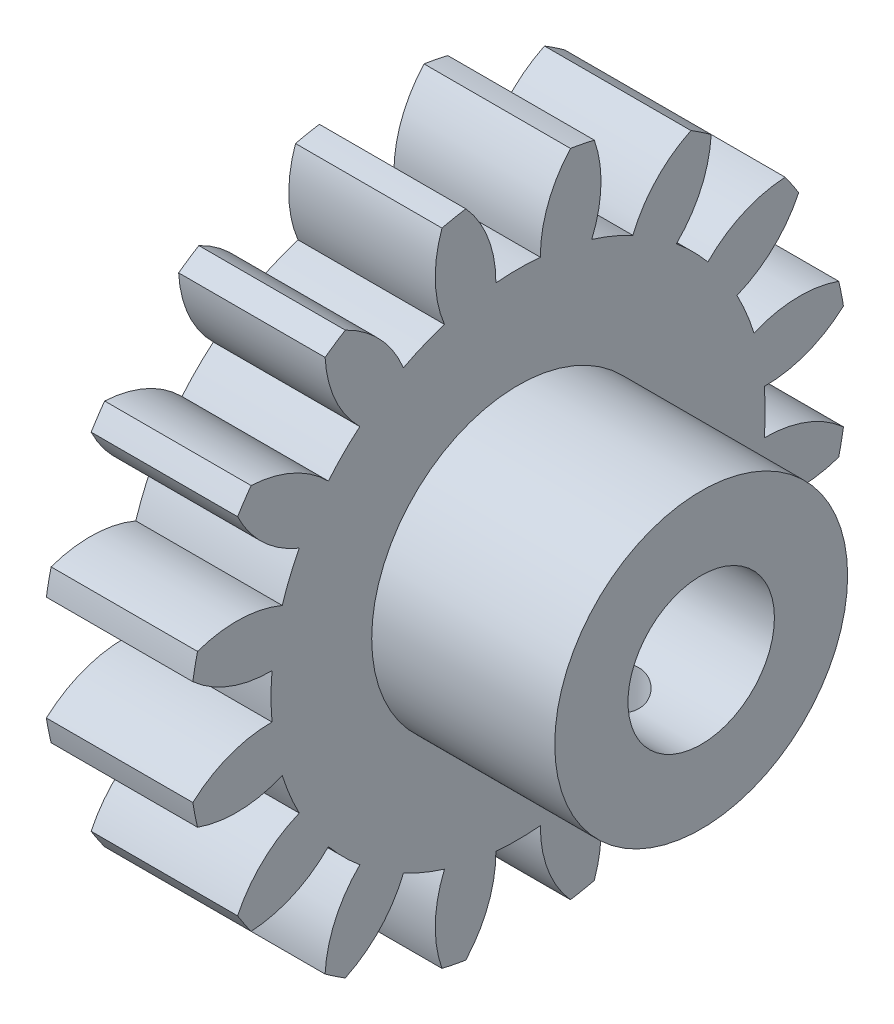
SolidWorks part; units mm, degrees
ref_plane "Plane1" through (0, 0, 0) normal (0, 0, 1) x (1, 0, 0)
ref_plane "Plane2" through (0, 0, 0) normal (0, 1, 0) x (1, 0, 0)
ref_plane "Plane3" through (0, 0, 0) normal (1, 0, 0) x (0, 0, -1)
other "Configuration Table"
sketch "HoldingSke" plane through (0, 0, 0) normal (0, 1, 0) x (1, 0, 0)
  line L0 (0, 0) -> (0.3845, -0.1103)
  line L1 (-15, 0) -> (100, 0) construction
  line L2 (0, 0) -> (-2.1039, 2.3779)
  line L3 (0, 0) -> (-11.863, 4.5341)
  line L4 (0, 0) -> (8.3015, 2.3804)
  line L5 (0, 0) -> (-46.8476, -17.4728)
  line L6 (0, 0) -> (-8.2896, -5.593)
  line L7 (-2.1039, 2.3779) -> (8.6586, 51.2059)
  line L8 (-76.2, 54.61) -> (-74.4, 54.61)
  line L9 (-67.7845, 28.3722) -> (-49.3413, 33.142)
  line L10 (-76.2, 71.12) -> (104.1128, 71.12)
  line L11 (0, 0) -> (-10, 0)
  line L12 (-76.2, 101.6) -> (-76.113, 101.6)
  line L13 (24.9733, 27.94) -> (52.9518, 28.4284)
  line L14 (24.9733, 27.94) -> (24.9743, 27.94)
  line L15 (24.9733, 27.94) -> (100.4006, 29.5858)
  line L16 (-63.627, -2.5) -> (-12.827, -2.5)
  circle A0 centre (0, 0) radius 5
  circle A1 centre (0, 0) radius 16.874
  circle A2 centre (0, 0) radius 37.5
  circle A3 centre (0, 0) radius 5
  dimension "MHD" = 33.748
  dimension "Hub_dia" = 75
  dimension "Bore" = 10
  dimension "MBD" = 10
  dimension "Num_teeth" = 16
  dimension "Pitch" = 0.4
  dimension "Overall_len" = 50
  dimension "Show_teeth" = 16
  dimension "Thickness" = 10
  dimension "OAL" = 50.0001
  dimension "T_dim" = 1.8
  dimension "Ap" = 14.5
  dimension "H" = 19.05
  dimension "Pitch_radius" = 180.3128
  dimension "Width" = 10
  dimension "Backlash" = 0.087
  dimension "Addendum_fac" = 1
  dimension "Dedendum_fac" = 1.25
  dimension "Clearance_fac" = 0.25
  dimension "Dedendum_add" = 0.001
  dimension "Module" = 2.5
sketch "BasProSke" plane through (0, 0, 0) normal (0, 1, 0) x (1, 0, 0)
  line L0 (-10, 0) -> (60, 0) construction
  line L1 (0, 0) -> (0, 22.5)
  line L2 (0, 0) -> (10, 0)
  line L3 (10, 0) -> (10, 22.5)
  line L4 (10, 22.5) -> (0, 22.5)
  dimension "Thickness" = 10
  dimension "Diameter" = 45
revolve "Base-Revolve" add sketch "BasProSke" angle 360 about L0
sketch "TooCutSke" plane through (0, 0, 0) normal (1, 0, 0) x (0, 0, -1)
  line L1 (0, 0) -> (0, 107) construction
  line L2 (0, 0) -> (-2.1125, 19.8881) construction
  line L3 (0, 0) -> (-7.7717, 39.0708) construction
  line L4 (-2.1125, 19.8881) -> (-3.8858, 19.5354) construction
  arc A0 (1.5183, 16.8056) -> (-1.5183, 16.8056) centre (0, 0) ccw
  arc A1 (3.5927, 22.237) -> (-3.5927, 22.237) centre (0, 0) ccw
  circle A2 centre (0, 0) radius 20 construction
  circle A3 centre (0, 0) radius 19.363 construction
  arc A4 (-1.5183, 16.8056) -> (-3.5927, 22.237) centre (-9.5181, 16.8621) ccw
  arc A5 (3.5927, 22.237) -> (1.5183, 16.8056) centre (9.5181, 16.8621) ccw
  dimension "Root_dia" = 33.748
  dimension "Overcut_dia" = 45.0508
  dimension "Pitch_dia" = 40
  dimension "Base_dia" = 38.7259
  dimension "Flank_rad" = 8
  dimension "Half_ang" = 11.25
  dimension "Half_CT" = 1.8081
extrude "ToothCut" cut sketch "TooCutSke" along normal through all
fillet "Breaks" [suppressed] radius 0.05
fillet "RootFillets" [suppressed] radius 0.626
pattern_circular "TeethCuts" count 16 every 22.5 about axis through (-10, 0, 0) along (1, 0, 0) of "ToothCut", "RootFillets", "Breaks"
sketch "HubNeaOneSke" plane through (0, 0, 0) normal (-1, 0, 0) x (0, 0, 1)
  circle A0 centre (0, 0) radius 16.874
  dimension "Diameter" = 33.748
extrude "HubNearOne" [suppressed] add sketch "HubNeaOneSke" along normal blind 40.0001
sketch "HubNeaBotSke" plane through (0, 0, 0) normal (-1, 0, 0) x (0, 0, 1)
  circle A0 centre (0, 0) radius 16.874
  dimension "Diameter" = 33.748
extrude "HubNearBoth" [suppressed] add sketch "HubNeaBotSke" along normal blind 20
ref_plane "FarPln" through (10, 0, 0) normal (1, 0, 0) x (0, 0, -1)
sketch "HubFarSke" plane through (10, 0, 0) normal (1, 0, 0) x (0, 0, -1)
  circle A0 centre (0, 0) radius 16.874
  dimension "Diameter" = 33.748
extrude "HubFar" [suppressed] add sketch "HubFarSke" along normal blind 20
sketch "BorSke" plane through (0, 0, 0) normal (1, 0, 0) x (0, 0, -1)
  circle A0 centre (0, 0) radius 5
  dimension "Diameter" = 10
extrude "Bore" cut sketch "BorSke" along normal mid plane 100.0001
sketch "KeySke" plane through (0, 0, 0) normal (1, 0, 0) x (0, 0, -1)
  line L0 (-2, 0) -> (-2, 6.8)
  line L1 (-2, 6.8) -> (2, 6.8)
  line L2 (2, 6.8) -> (2, 0)
  line L3 (0, 0) -> (0, 34) construction
  line L4 (-2, 0) -> (2, 0)
  dimension "Offset" = 6.8
  dimension "Width" = 4
extrude "Keyway" [suppressed] cut sketch "KeySke" along normal mid plane 100.0001
pattern_circular "Keyway2" [suppressed] count 2 every 90 about axis through (-10, 0, 0) along (1, 0, 0)
sketch "Esquisse1" plane through (10, 0, 0) normal (1, 0, 0) x (0, 0, -1)
  circle A0 centre (0, 0) radius 10
  circle A1 centre (0, 0) radius 5
extrude "Boss.-Extru.1" add sketch "Esquisse1" along normal blind 12.5
sketch "Esquisse2" plane through (0, 0, 0) normal (0, 1, 0) x (1, 0, 0)
  line L0 (22.5, -10) -> (22.5, 10) construction
  circle A0 centre (16.25, 0) radius 2
  dimension "D1" = 4
  dimension "D2" = 6.25
extrude "Enlèv. mat.-Extru.1" cut sketch "Esquisse2" against normal blind 12.5
equation "' \"Module@HoldingSke\" = 6.35"
equation "' \"Num_teeth@HoldingSke\" = 12"
equation "' \"Ap@HoldingSke\" =  20"
equation "' \"Ap@HoldingSke\" = 20"
equation "' \"Width@HoldingSke\" = 0.5 * 25.4"
equation "' \"Hub_dia@HoldingSke\"= 1 * 25.4"
equation "' \"Hub_dia@HoldingSke\" = 1 * 25.4"
equation "' \"Overall_len@HoldingSke\" = 1.0 * 25.4"
equation "' \"Bore@HoldingSke\" = 0.75 * 25.4"
equation "' \"T_dim@HoldingSke\" = 0.1 * 25.4"
equation "' \"Width@KeySke\" = 0.25 * 25.4"
equation "' \"Show_teeth@HoldingSke\" = 13"
equation "' \"Backlash@HoldingSke\" = 0.009 * 25.4"
equation "' \"Addendum_fac@HoldingSke\" = 1.0"
equation "' \"Dedendum_fac@HoldingSke\" = 1.25"
equation "' \"Dedendum_add@HoldingSke\" = 0.00005 * 25.4"
equation "' \"Clearance_fac@HoldingSke\" = 0.25"
equation "\"Pitch@HoldingSke\" = 1 / \"Module@HoldingSke\""
equation "\"Overcut_dia@TooCutSke\" = (\"Num_teeth@HoldingSke\" + 2 * \"Addendum_fac@HoldingSke\") / \"Pitch@HoldingSke\" + 0.002 * 25.4"
equation "\"Pitch_dia@TooCutSke\" = \"Num_teeth@HoldingSke\" / \"Pitch@HoldingSke\""
equation "\"Base_dia@TooCutSke\" = \"Num_teeth@HoldingSke\" / \"Pitch@HoldingSke\" * cos((\"Ap@HoldingSke\"  * 3.14159265 / 180))"
equation "\"Root_dia@TooCutSke\" = (\"Num_teeth@HoldingSke\" + 2) / \"Pitch@HoldingSke\" - 2 * (\"Addendum_fac@HoldingSke\" + \"Dedendum_fac@HoldingSke\") / \"Pitch@HoldingSke\" - \"Dedendum_add@HoldingSke\" * 2"
equation "\"Half_ang@TooCutSke\" = 180 / \"Num_teeth@HoldingSke\""
equation "\"Half_CT@TooCutSke\" = \"Num_teeth@HoldingSke\" / \"Pitch@HoldingSke\" * sin((3.14159265 / 2 / \"Num_teeth@HoldingSke\")) / 2 - 7 * \"Backlash@HoldingSke\" / 4"
equation "\"Flank_rad@TooCutSke\" = \"Num_teeth@HoldingSke\" / \"Pitch@HoldingSke\" / 5"
equation "\"Radius@RootFillets\" = \"Clearance_fac@HoldingSke\" / \"Pitch@HoldingSke\" + \"Dedendum_add@HoldingSke\""
equation "\"Break_rad@Breaks\" = 0.02 / \"Pitch@HoldingSke\""
equation "\"Thickness@HoldingSke\" = \"Width@HoldingSke\""
equation "\"OAL@HoldingSke\" = \"Thickness@HoldingSke\""
equation "\"MHD@HoldingSke\" = (\"Num_teeth@HoldingSke\" + 2) / \"Pitch@HoldingSke\" - 2 * (\"Addendum_fac@HoldingSke\" + \"Dedendum_fac@HoldingSke\")  / \"Pitch@HoldingSke\" - \"Dedendum_add@HoldingSke\" * 2"
equation "\"MBD@HoldingSke\" = (\"Num_teeth@HoldingSke\" + 2) / \"Pitch@HoldingSke\" - 2 * (\"Addendum_fac@HoldingSke\" + \"Dedendum_fac@HoldingSke\")  / \"Pitch@HoldingSke\" - \"Dedendum_add@HoldingSke\" * 2 - 0.002 * 25.4"
equation "\"MHD@HoldingSke\" = ((sgn( \"MHD@HoldingSke\" - \"Hub_dia@HoldingSke\" )-1)*( \"MHD@HoldingSke\" - \"Hub_dia@HoldingSke\" ))/-2+ \"Hub_dia@HoldingSke\""
equation "\"MBD@HoldingSke\" = ((sgn( \"MBD@HoldingSke\" - \"Bore@HoldingSke\" )-1)*( \"MBD@HoldingSke\" - \"Bore@HoldingSke\" ))/-2+ \"Bore@HoldingSke\""
equation "\"OAL@HoldingSke\" = ((sgn( \"OAL@HoldingSke\" - \"Overall_len@HoldingSke\" )+1)*( \"OAL@HoldingSke\" - \"Overall_len@HoldingSke\" ))/2 + \"Overall_len@HoldingSke\" + 0.000002 * 25.4"
equation "\"Num_teeth@TeethCuts\" = int( \"Show_teeth@HoldingSke\" ) + 1"
equation "\"Num_teeth@TeethCuts\" = ((sgn( \"Num_teeth@TeethCuts\" - \"Num_teeth@HoldingSke\" )-1)*( \"Num_teeth@TeethCuts\" - \"Num_teeth@HoldingSke\" ))/-2+ \"Num_teeth@HoldingSke\""
equation "\"Num_teeth@TeethCuts\" = ((sgn( \"Num_teeth@TeethCuts\" - 2.0)+1)*( \"Num_teeth@TeethCuts\" - 2.0))/2 +2.0"
equation "\"Angle@TeethCuts\" = 360.0 / \"Num_teeth@HoldingSke\""
equation "\"Diameter@BasProSke\" = (\"Num_teeth@HoldingSke\" + 2 * \"Addendum_fac@HoldingSke\") / \"Pitch@HoldingSke\""
equation "\"Thickness@BasProSke\"  = \"Thickness@HoldingSke\""
equation "' \"Fillet_rad@BasProSke\" =  \"Thickness@HoldingSke\" * 0.05"
equation "' \"Fillet_rad@BasProSke\" = \"Thickness@HoldingSke\" * 0.05"
equation "\"MHD@HoldingSke\" = ((sgn( \"MHD@HoldingSke\" - \"Root_dia@TooCutSke\" )-1)*( \"MHD@HoldingSke\" - \"Root_dia@TooCutSke\" ))/-2+ \"Root_dia@TooCutSke\""
equation "\"Diameter@HubNeaOneSke\" = \"MHD@HoldingSke\""
equation "\"Length@HubNearOne\" = \"OAL@HoldingSke\" - \"Thickness@BasProSke\""
equation "\"Diameter@HubNeaBotSke\" = \"MHD@HoldingSke\""
equation "\"Length@HubNearBoth\" = ( \"OAL@HoldingSke\" - \"Thickness@BasProSke\" ) / 2.0"
equation "\"Thickness@FarPln\" = \"Thickness@BasProSke\""
equation "\"Diameter@HubFarSke\" = \"MHD@HoldingSke\""
equation "\"Length@HubFar\" = ( \"OAL@HoldingSke\" - \"Thickness@BasProSke\" ) / 2.0"
equation "\"Diameter@BorSke\" = \"MBD@HoldingSke\""
equation "\"D1@Bore\" = \"OAL@HoldingSke\" * 2.0"
equation "\"D1@Keyway\" = \"OAL@HoldingSke\" * 2.0"
equation "\"Offset@KeySke\" = \"T_dim@HoldingSke\" + \"MBD@HoldingSke\" / 2.0"
